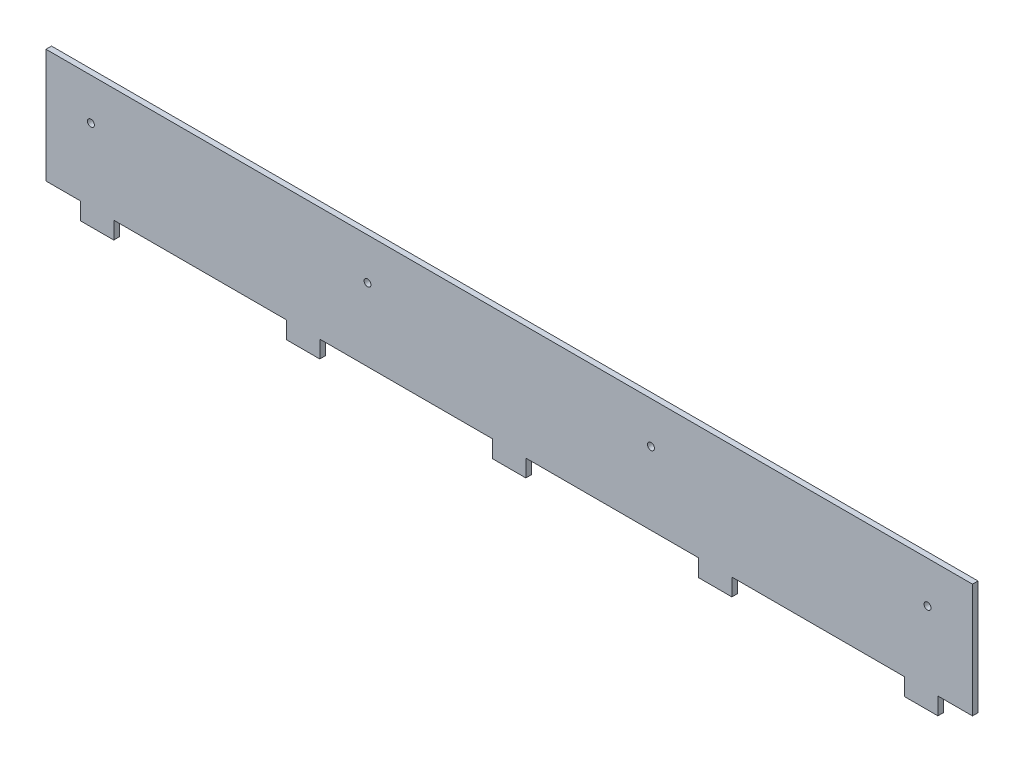
SolidWorks part; units mm, degrees
ref_plane "Спереди" through (0, 0, 0) normal (0, 0, 1) x (1, 0, 0)
ref_plane "Сверху" through (0, 0, 0) normal (0, 1, 0) x (1, 0, 0)
ref_plane "Справа" through (0, 0, 0) normal (1, 0, 0) x (0, 0, -1)
sketch "Эскиз1" plane through (0, 0, 0) normal (0, 0, 1) x (1, 0, 0)
  line L1 (-335, -47.5) -> (335, -47.5)
  line L2 (-335, -47.5) -> (-335, 47.5)
  line L3 (-335, 47.5) -> (335, 47.5)
  line L4 (335, -47.5) -> (335, 47.5)
  line L5 (0, 47.5) -> (0, -47.5) construction
  line L6 (-335, 0) -> (335, 0) construction
  point P0 (0, 0)
  dimension "D1" = 95
  dimension "D2" = 670
extrude "Бобышка-Вытянуть1" add sketch "Эскиз1" along normal mid plane 4
sketch "Эскиз2" plane through (0, 0, 2) normal (0, 0, 1) x (1, 0, 0)
  line L0 (-335, -47.5) -> (335, -47.5) construction
  line L9 (-435, -35.0456) -> (-310, -35.0456)
  line L10 (-435, -35.0456) -> (-435, -47.5)
  line L11 (-435, -47.5) -> (-310, -47.5)
  line L12 (-310, -35.0456) -> (-310, -47.5)
  line L14 (-286, -35.0456) -> (-161, -35.0456)
  line L15 (-286, -35.0456) -> (-286, -47.5)
  line L16 (-286, -47.5) -> (-161, -47.5)
  line L17 (-161, -35.0456) -> (-161, -47.5)
  line L18 (-137, -35.0456) -> (-12, -35.0456)
  line L19 (-137, -35.0456) -> (-137, -47.5)
  line L20 (-137, -47.5) -> (-12, -47.5)
  line L21 (-12, -35.0456) -> (-12, -47.5)
  line L22 (12, -35.0456) -> (137, -35.0456)
  line L23 (12, -35.0456) -> (12, -47.5)
  line L24 (12, -47.5) -> (137, -47.5)
  line L25 (137, -35.0456) -> (137, -47.5)
  line L26 (161, -35.0456) -> (286, -35.0456)
  line L27 (161, -35.0456) -> (161, -47.5)
  line L28 (161, -47.5) -> (286, -47.5)
  line L29 (286, -35.0456) -> (286, -47.5)
  line L30 (310, -35.0456) -> (435, -35.0456)
  line L31 (310, -35.0456) -> (310, -47.5)
  line L32 (310, -47.5) -> (435, -47.5)
  line L33 (435, -35.0456) -> (435, -47.5)
  point P25 (-137, -41.2728)
  point P26 (137, -41.2728)
  dimension "D6" = 125
  dimension "D3" = 125
  dimension "D4" = 125
  dimension "D9" = 125
  dimension "D11" = 125
  dimension "D5" = 24
  dimension "D2" = 24
  dimension "D7" = 24
  dimension "D8" = 24
  dimension "D10" = 24
  dimension "D12" = 125
  dimension "D13" = 12
extrude "Вырез-Вытянуть1" cut sketch "Эскиз2" against normal through all
sketch "Эскиз3" [suppressed] plane through (0, 0, 2) normal (0, 0, 1) x (1, 0, 0)
  line L0 (-328, 5.9544) -> (-328, -6.0456)
  line L1 (-328, -6.0456) -> (-318, -6.0456)
  line L2 (-318, -6.0456) -> (-318, -20.0456)
  line L3 (-318, -20.0456) -> (318, -20.0456)
  line L4 (318, -20.0456) -> (318, -6.0456)
  line L5 (318, -6.0456) -> (328, -6.0456)
  line L6 (328, -6.0456) -> (328, 5.9544)
  line L7 (328, 5.9544) -> (290, 5.9544)
  line L8 (290, 5.9544) -> (280, 35.5)
  line L9 (280, 35.5) -> (240, 35.5)
  line L10 (240, 35.5) -> (230, 5.9544)
  line L11 (230, 5.9544) -> (-230, 5.9544)
  line L12 (-230, 5.9544) -> (-240, 35.5)
  line L13 (-240, 35.5) -> (-280, 35.5)
  line L14 (-280, 35.5) -> (-290, 5.9544)
  line L15 (-290, 5.9544) -> (-328, 5.9544)
  line L16 (0, 0) -> (0, 91.1092) construction
  line L17 (-260, 35.5) -> (-260, 12.7826) construction
  line L18 (260, 35.5) -> (260, 0) construction
  line L19 (-12, -35.0456) -> (-137, -35.0456) construction
  line L20 (-335, 47.5) -> (-335, -35.0456) construction
  line L21 (335, 47.5) -> (-335, 47.5) construction
  dimension "D1" = 15
  dimension "D2" = 14
  dimension "D3" = 12
  dimension "D4" = 60
  dimension "D5" = 38
  dimension "D6" = 7
  dimension "D7" = 17
  dimension "D8" = 12
  dimension "D9" = 40
extrude "Вырез-Вытянуть2" [suppressed] cut sketch "Эскиз3" against normal through all
fillet "Скругление1" [suppressed] radius 10
fillet "Скругление6" [suppressed] radius 2
sketch "Эскиз4" [suppressed] plane through (0, 0, 2) normal (0, 0, 1) x (1, 0, 0)
  circle A1 centre (-302.5, -27.5) radius 2.5
  circle A2 centre (-302.5, -27.5) radius 2.5
  circle A3 centre (0, -27.5) radius 2.5
  circle A4 centre (0, -27.5) radius 2.5
  circle A5 centre (302.5, -27.5) radius 2.5
  circle A6 centre (302.5, -27.5) radius 2.5
  circle A7 centre (-102.5, 17.5) radius 2.5
  circle A8 centre (-102.5, 17.5) radius 2.5
  circle A9 centre (102.5, 17.5) radius 2.5
  circle A10 centre (102.5, 17.5) radius 2.5
  circle A11 centre (-302.5, 17.5) radius 2.5
  circle A12 centre (-302.5, 17.5) radius 2.5
  circle A13 centre (302.5, 17.5) radius 2.5
  circle A14 centre (302.5, 17.5) radius 2.5
  dimension "D1" = 0
  dimension "D2" = 0
  dimension "D3" = 0
  dimension "D4" = 0
  dimension "D5" = 0
  dimension "D6" = 0
  dimension "D7" = 0
extrude "Вырез-Вытянуть3" [suppressed] cut sketch "Эскиз4" against normal through all
sketch "Эскиз5" plane through (0, 0, 2) normal (0, 0, 1) x (1, 0, 0)
  circle A7 centre (-102.5, 17.5) radius 2.5
  circle A8 centre (-102.5, 17.5) radius 2.5
  circle A9 centre (102.5, 17.5) radius 2.5
  circle A10 centre (102.5, 17.5) radius 2.5
  circle A11 centre (-302.5, 17.5) radius 2.5
  circle A12 centre (-302.5, 17.5) radius 2.5
  circle A13 centre (302.5, 17.5) radius 2.5
  circle A14 centre (302.5, 17.5) radius 2.5
  dimension "D4" = 0
  dimension "D5" = 0
  dimension "D6" = 0
  dimension "D7" = 0
extrude "Вырез-Вытянуть4" cut sketch "Эскиз5" against normal through all
equation "\"D3@Эскиз2\"=\"D6@Эскиз2\""
equation "\"D4@Эскиз2\"=\"D6@Эскиз2\""
equation "\"D9@Эскиз2\"=\"D6@Эскиз2\""
equation "\"D2@Эскиз2\"=\"D5@Эскиз2\""
equation "\"D7@Эскиз2\"=\"D5@Эскиз2\""
equation "\"D10@Эскиз2\"=\"D5@Эскиз2\""
equation "\"D12@Эскиз2\"=\"D6@Эскиз2\""
equation "\"D13@Эскиз2\"=\"D5@Эскиз2\"/2"
